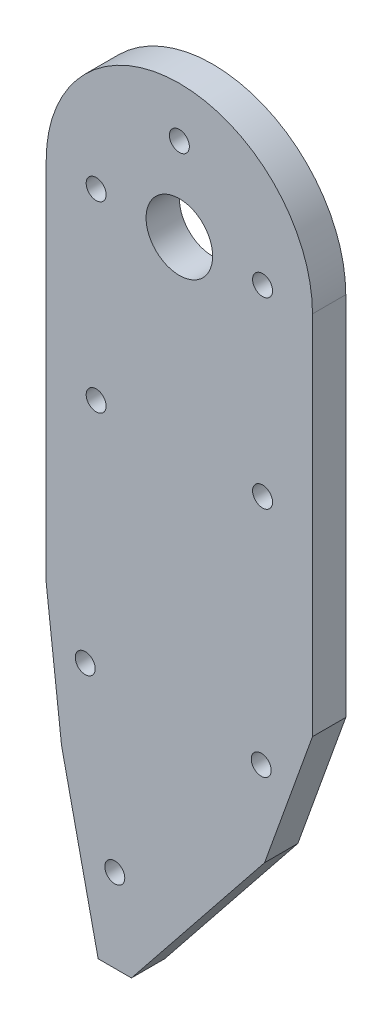
SolidWorks part; units mm, degrees
ref_plane "前视基准面" through (0, 0, 0) normal (0, 0, 1) x (1, 0, 0)
ref_plane "上视基准面" through (0, 0, 0) normal (0, 1, 0) x (1, 0, 0)
ref_plane "右视基准面" through (0, 0, 0) normal (1, 0, 0) x (0, 0, -1)
sketch "草图1" plane through (0, 0, 0) normal (0, 0, 1) x (1, 0, 0)
  line L0 (-22.2822, 49.7411) -> (-22.2822, -5.2589)
  line L1 (-22.2822, -5.2589) -> (-19.9822, -25.2589)
  line L2 (-19.9822, -25.2589) -> (-14.4822, -50.2589)
  line L3 (-14.4822, -50.2589) -> (-9.4822, -50.2589)
  line L4 (-9.4822, -50.2589) -> (10.5178, -25.2589)
  line L5 (10.5178, -25.2589) -> (17.7178, -5.2589)
  line L6 (17.7178, -5.2589) -> (17.7178, 49.7411)
  line L7 (17.7178, 49.7411) -> (-22.2822, 49.7411) construction
  line L8 (-22.2822, -5.2589) -> (17.7178, -5.2589) construction
  line L9 (-19.9822, -25.2589) -> (10.5178, -25.2589) construction
  arc A0 (17.7178, 49.7411) -> (-22.2822, 49.7411) centre (-2.2822, 49.7411) ccw
  dimension "D2" = 20
  dimension "D1" = 55
extrude "凸台-拉伸1" add sketch "草图1" along normal blind 5
sketch "草图2" plane through (0, 0, 5) normal (0, 0, 1) x (1, 0, 0)
  line L7 (-22.2822, 49.7411) -> (-22.2822, -5.2589)
  line L8 (-22.2822, -5.2589) -> (-19.9822, -25.2589)
  line L9 (-19.9822, -25.2589) -> (-14.4822, -50.2589)
  line L10 (-14.4822, -50.2589) -> (-9.4822, -50.2589)
  line L11 (-9.4822, -50.2589) -> (10.5178, -25.2589)
  line L12 (10.5178, -25.2589) -> (17.7178, -5.2589)
  line L13 (17.7178, -5.2589) -> (17.7178, 49.7411)
  line L14 (-22.2822, 49.7411) -> (-22.2822, -5.2589) construction
  line L15 (-22.2822, -5.2589) -> (-19.9822, -25.2589) construction
  line L16 (-19.9822, -25.2589) -> (-14.4822, -50.2589) construction
  line L17 (-14.4822, -50.2589) -> (-9.4822, -50.2589) construction
  line L18 (-9.4822, -50.2589) -> (10.5178, -25.2589) construction
  line L19 (10.5178, -25.2589) -> (17.7178, -5.2589) construction
  line L20 (17.7178, -5.2589) -> (17.7178, 49.7411) construction
  circle A0 centre (-2.2822, 49.7411) radius 5
  arc A1 (17.7178, 49.7411) -> (-22.2822, 49.7411) centre (-2.2822, 49.7411) ccw
  arc A2 (17.7178, 49.7411) -> (-22.2822, 49.7411) centre (-2.2822, 49.7411) ccw construction
  dimension "D2" = 10
  dimension "D1" = 0
extrude "切除-拉伸1" cut sketch "草图2" against normal up to surface (5 mm away) contours A0 up to face at (-5.3197, -5.2589, 0)
sketch "草图3" plane through (0, 0, 5) normal (0, 0, 1) x (1, 0, 0)
  line L0 (-19.9822, -25.2589) -> (10.5178, -25.2589) construction
  line L1 (-11.9822, -50.2589) -> (-11.9822, -25.2589) construction
  line L2 (-14.4822, -50.2589) -> (-9.4822, -50.2589) construction
  line L3 (17.7178, -5.2589) -> (-22.2822, -5.2589) construction
  line L4 (10.5178, -25.2589) -> (10.5178, -5.2589) construction
  line L5 (-11.9822, -25.2589) -> (-11.9822, -5.2589) construction
  line L6 (-22.2822, 49.7411) -> (-7.2822, 49.7411) construction
  line L7 (-14.7822, 49.7411) -> (-14.7822, -5.2589) construction
  line L8 (-2.2822, 69.7411) -> (-2.2822, 54.7411) construction
  line L9 (2.7178, 49.7411) -> (17.7178, 49.7411) construction
  line L10 (-14.7822, 22.2411) -> (10.2178, 22.2411) construction
  line L11 (-6.4197, -5.2589) -> (-6.4197, -20.2589) construction
  line L12 (-6.4197, -12.7589) -> (15.0178, -12.7589) construction
  line L13 (10.5178, -25.2589) -> (17.7178, -5.2589) construction
  line L14 (-6.4197, -12.7589) -> (-21.4197, -12.7589) construction
  line L15 (-22.2822, -5.2589) -> (-19.9822, -25.2589) construction
  line L16 (-21.4197, -12.7589) -> (-11.9822, -12.7589) construction
  line L17 (15.0178, -12.7589) -> (4.299, -12.7589) construction
  line L18 (-21.4197, -12.7589) -> (-16.4197, -12.7589) construction
  line L19 (-2.2822, -5.2589) -> (-2.2822, -25.2589) construction
  line L20 (15.0178, -12.7589) -> (10.0178, -12.7589) construction
  circle A0 centre (-11.9822, -37.7589) radius 1.5
  circle A3 centre (-2.2822, 49.7411) radius 5 construction
  arc A4 (17.7178, 49.7411) -> (-22.2822, 49.7411) centre (-2.2822, 49.7411) ccw construction
  circle A5 centre (-14.7822, 49.7411) radius 1.5
  circle A6 centre (10.2178, 49.7411) radius 1.5
  circle A7 centre (-2.2822, 62.2411) radius 1.5
  circle A8 centre (10.2178, 22.2411) radius 1.5
  circle A9 centre (-14.7822, 22.2411) radius 1.5
  circle A10 centre (-16.4197, -12.7589) radius 1.5
  circle A11 centre (10.0178, -12.7589) radius 1.5
  dimension "D1" = 15
  dimension "D2" = 3
  dimension "D3" = 3
  dimension "D4" = 3
  dimension "D5" = 3
  dimension "D6" = 3
  dimension "D7" = 3
  dimension "D10" = 3
  dimension "D12" = 3
  dimension "D8" = 15
  dimension "D9" = 5
  dimension "D11" = 5
extrude "切除-拉伸2" cut sketch "草图3" against normal up to next
